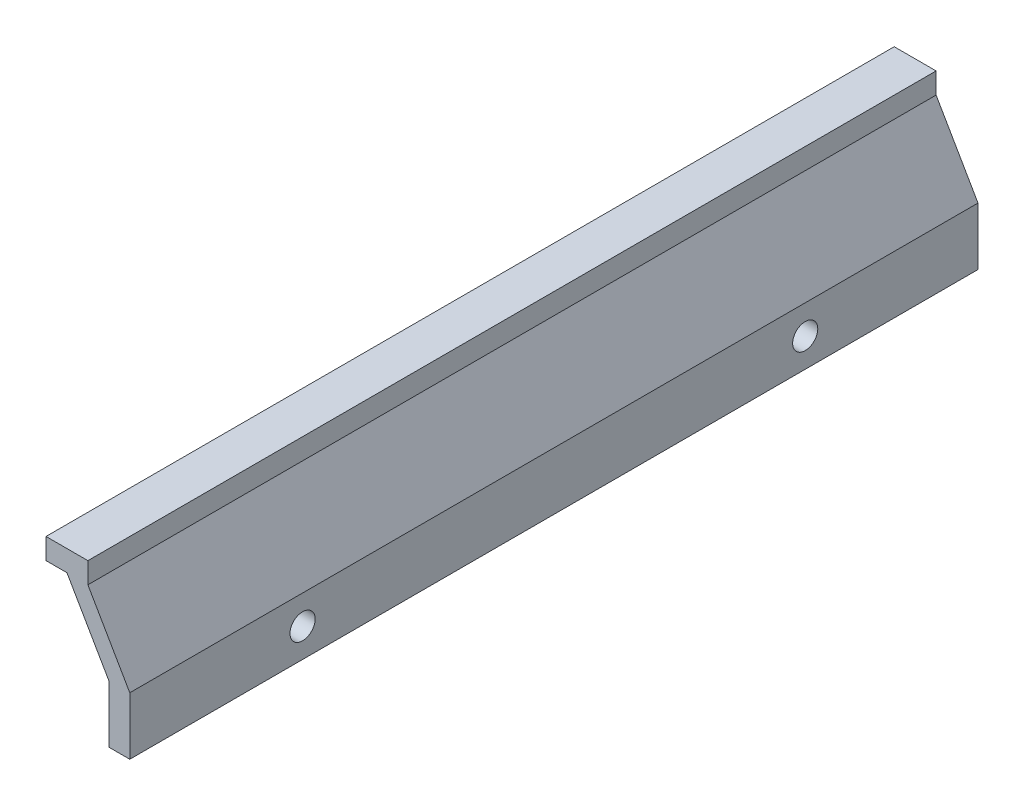
SolidWorks part; units mm, degrees
material "ABS"
ref_plane "正面" through (0, 0, 0) normal (0, 0, 1) x (1, 0, 0)
ref_plane "平面" through (0, 0, 0) normal (0, 1, 0) x (1, 0, 0)
ref_plane "右側面" through (0, 0, 0) normal (1, 0, 0) x (0, 0, -1)
sketch "ｽｹｯﾁ1" plane through (0, 0, 0) normal (0, 0, 1) x (1, 0, 0)
  line L0 (-5, 9.6782) -> (-1, 2.75)
  line L1 (1, -2.75) -> (-1, -2.75)
  line L2 (1, -2.75) -> (1, 2.75)
  line L4 (-1, -2.75) -> (-1, 2.75)
  line L5 (1, -2.75) -> (-1, 2.75) construction
  line L6 (1, 2.75) -> (-1, -2.75) construction
  line L7 (-3, 11.6782) -> (-5, 11.6782)
  line L8 (-3, 11.6782) -> (-3, 9.6782)
  line L11 (-3, 11.6782) -> (-5, 9.6782) construction
  line L12 (-3, 9.6782) -> (-5, 11.6782) construction
  line L13 (-3, 9.6782) -> (1, 2.75)
  line L14 (-5, 9.6782) -> (-7, 9.6782)
  line L15 (-7, 9.6782) -> (-7, 11.6782)
  line L16 (-7, 11.6782) -> (-5, 11.6782)
  point P0 (0, 0)
  point P6 (-4, 10.6782)
  dimension "D1" = 2
  dimension "D2" = 5.5
  dimension "D3" = 8
  dimension "D4" = 150
extrude "ﾎﾞｽ - 押し出し1" add sketch "ｽｹｯﾁ1" along normal blind 76 and the other way blind 5
sketch "ｽｹｯﾁ2" plane through (1, 0, 0) normal (1, 0, 0) x (0, 0, -1)
  line L0 (-76, 0) -> (5, 0) construction
  line L1 (-76, -2.75) -> (-76, 2.75) construction
  line L2 (5, -2.75) -> (5, 2.75) construction
  circle A0 centre (-59.5, 0) radius 1.2
  circle A1 centre (-11.5, 0) radius 1.2
  dimension "D1" = 2.4
  dimension "D2" = 2.4
  dimension "D3" = 16.5
  dimension "D4" = 16.5
extrude "ｶｯﾄ - 押し出し1" cut sketch "ｽｹｯﾁ2" against normal through all
